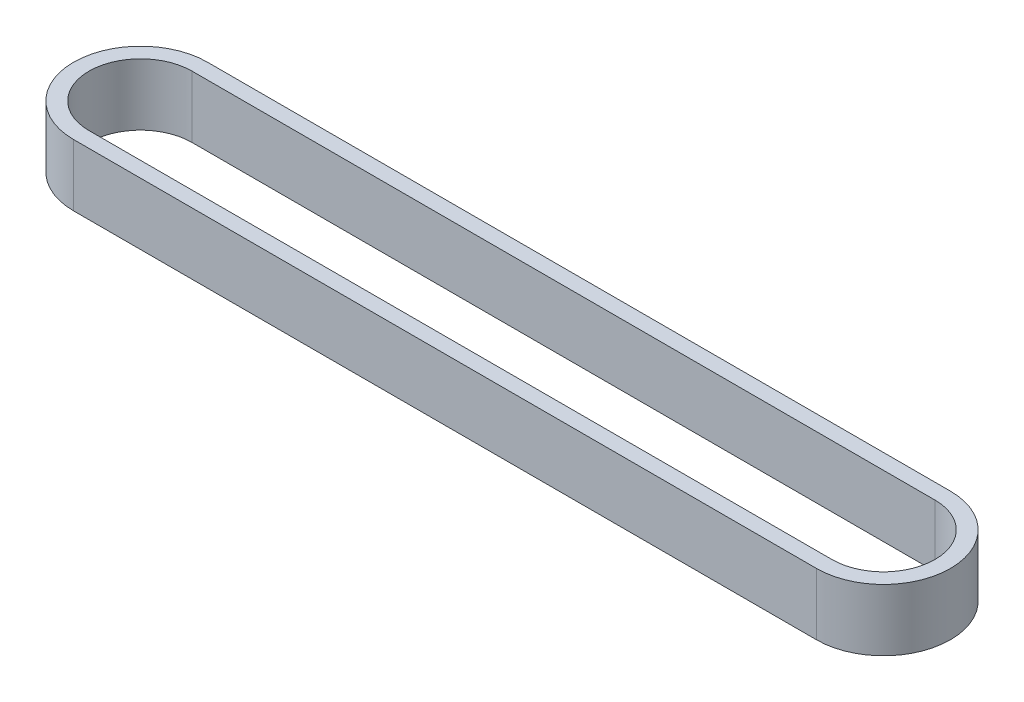
SolidWorks part; units mm, degrees
ref_plane "Front Plane" through (0, 0, 0) normal (0, 0, 1) x (1, 0, 0)
ref_plane "Top Plane" through (0, 0, 0) normal (0, 1, 0) x (1, 0, 0)
ref_plane "Right Plane" through (0, 0, 0) normal (1, 0, 0) x (0, 0, -1)
other "Default"
sketch "Sketch1" plane through (0, 0, 0) normal (0, 1, 0) x (1, 0, 0)
  line L0 (0, 5) -> (72.12, 5)
  line L1 (72.12, -5) -> (0, -5)
  line L2 (0, 6.5) -> (72.12, 6.5)
  line L3 (72.12, -6.5) -> (0, -6.5)
  arc A0 (0, 5) -> (0, -5) centre (0, 0) ccw
  arc A1 (72.12, 5) -> (72.12, -5) centre (72.12, 0) cw
  arc A2 (72.12, 6.5) -> (72.12, -6.5) centre (72.12, 0) cw
  arc A3 (0, 6.5) -> (0, -6.5) centre (0, 0) ccw
  dimension "R1" = 5
  dimension "R2" = 5
  dimension "CenterDistance" = 72.12
  dimension "Thickness" = 1.5
extrude "Boss-Extrude1" add sketch "Sketch1" along normal mid plane 6
